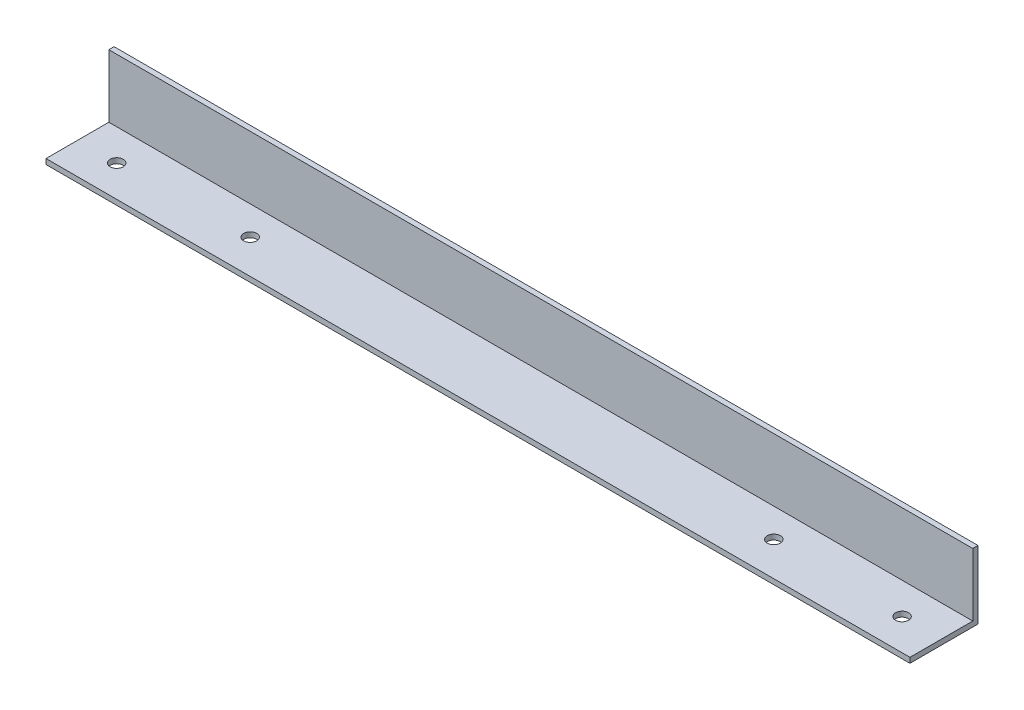
SolidWorks part; units mm, degrees
ref_plane "Front Plane" through (0, 0, 0) normal (0, 0, 1) x (1, 0, 0)
ref_plane "Top Plane" through (0, 0, 0) normal (0, 1, 0) x (1, 0, 0)
ref_plane "Right Plane" through (0, 0, 0) normal (1, 0, 0) x (0, 0, -1)
sketch "Sketch1" plane through (0, 0, 0) normal (1, 0, 0) x (0, 0, -1)
  line L0 (11, 13) -> (13, 13)
  line L1 (-13, 13) -> (13, 13) construction
  line L2 (-13, 13) -> (-13, -13) construction
  line L3 (-13, -13) -> (13, -13)
  line L4 (13, 13) -> (13, -13)
  line L5 (-13, 13) -> (13, -13) construction
  line L6 (-13, -13) -> (13, 13) construction
  line L7 (-13, 13) -> (11, 13) construction
  line L8 (-13, 13) -> (-13, -11) construction
  line L9 (-13, -11) -> (11, -11)
  line L10 (11, 13) -> (11, -11)
  line L11 (-13, -11) -> (-13, -13)
  point P0 (0, 0)
  dimension "D1" = 26
  dimension "D2" = 26
  dimension "D3" = 2
extrude "Boss-Extrude1" add sketch "Sketch1" along normal mid plane 330
sketch "Sketch2" plane through (0, 0, 0) normal (0, 1, 0) x (1, 0, 0)
  line L0 (165, 11) -> (165, -13) construction
  circle A0 centre (150, -1) radius 2.5
  dimension "D1" = 15
  dimension "D2" = 5
extrude "Cut-Extrude1" cut sketch "Sketch2" against normal through all
mirror "Mirror1" about plane through (0, 0, 0) normal (1, 0, 0) of "Cut-Extrude1"
sketch "Sketch3" plane through (0, 0, 0) normal (0, 1, 0) x (1, 0, 0)
  line L0 (0, 0) -> (100, 0) construction
  circle A0 centre (100, 0) radius 2.5
  dimension "D2" = 5
  dimension "D1" = 100
extrude "Cut-Extrude2" cut sketch "Sketch3" against normal through all
mirror "Mirror2" about plane through (0, 0, 0) normal (1, 0, 0) of "Cut-Extrude2"
equation "\"D2@Sketch1\"=\"w\""
equation "\"D1@Sketch1\"=\"w\""
equation "\"t\"= 2"
equation "\"w\"= 26"
equation "\"D3@Sketch1\"=\"t\""
